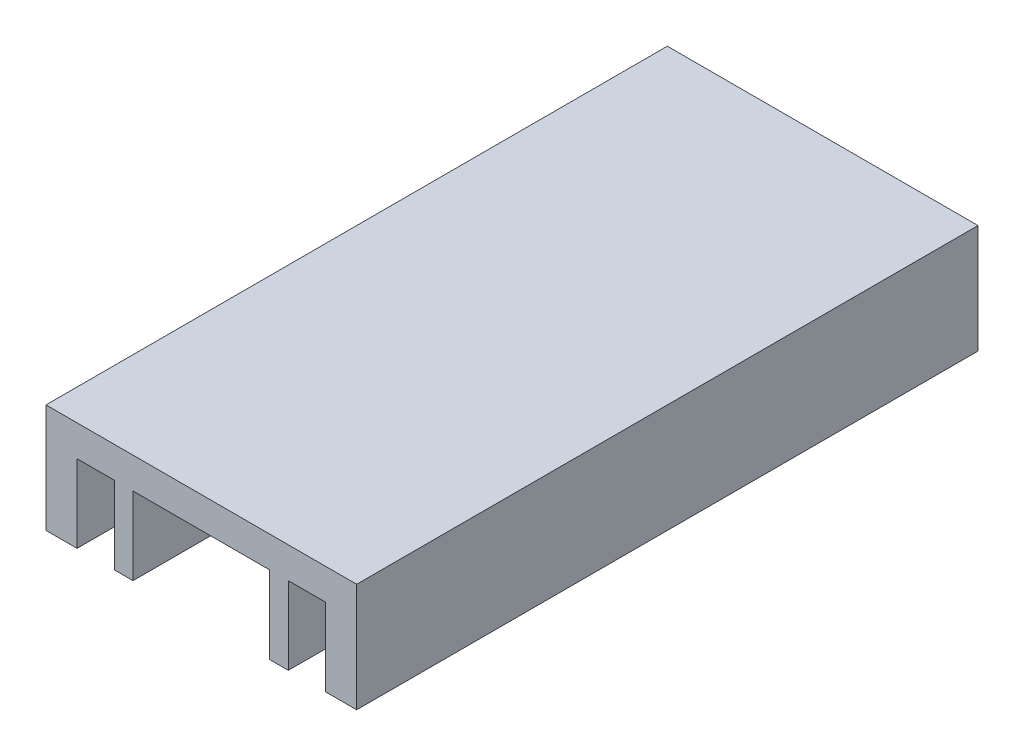
SolidWorks part; units mm, degrees
ref_plane "Front Plane" through (0, 0, 0) normal (0, 0, 1) x (1, 0, 0)
ref_plane "Top Plane" through (0, 0, 0) normal (0, 1, 0) x (1, 0, 0)
ref_plane "Right Plane" through (0, 0, 0) normal (1, 0, 0) x (0, 0, -1)
sketch "Sketch1" plane through (0, 0, 0) normal (0, 0, 1) x (1, 0, 0)
  line L0 (-3, 6.5) -> (-4, 6.5)
  line L1 (-4, 6.5) -> (-4, 10)
  line L2 (-4, 10) -> (6, 10)
  line L3 (6, 10) -> (6, 6.5)
  line L4 (6, 6.5) -> (5, 6.5)
  line L5 (5, 6.5) -> (5, 9)
  line L12 (-3, 6.5) -> (-3, 9)
  line L19 (-3, 9) -> (-1.8, 9)
  line L20 (-1.8, 9) -> (-1.8, 6.5)
  line L21 (-1.8, 6.5) -> (-1.2, 6.5)
  line L22 (-1.2, 6.5) -> (-1.2, 9)
  line L23 (-1.2, 9) -> (3.2, 9)
  line L24 (3.2, 9) -> (3.2, 6.5)
  line L25 (3.2, 6.5) -> (3.8, 6.5)
  line L26 (3.8, 6.5) -> (3.8, 9)
  line L27 (3.8, 9) -> (5, 9)
  dimension "D1" = 1
  dimension "D2" = 1
  dimension "D3" = 1.2
  dimension "D4" = 1.2
  dimension "D5" = 0.6
  dimension "D6" = 0.6
  dimension "D7" = 3.5
extrude "Boss-Extrude1" add sketch "Sketch1" along normal blind 20
